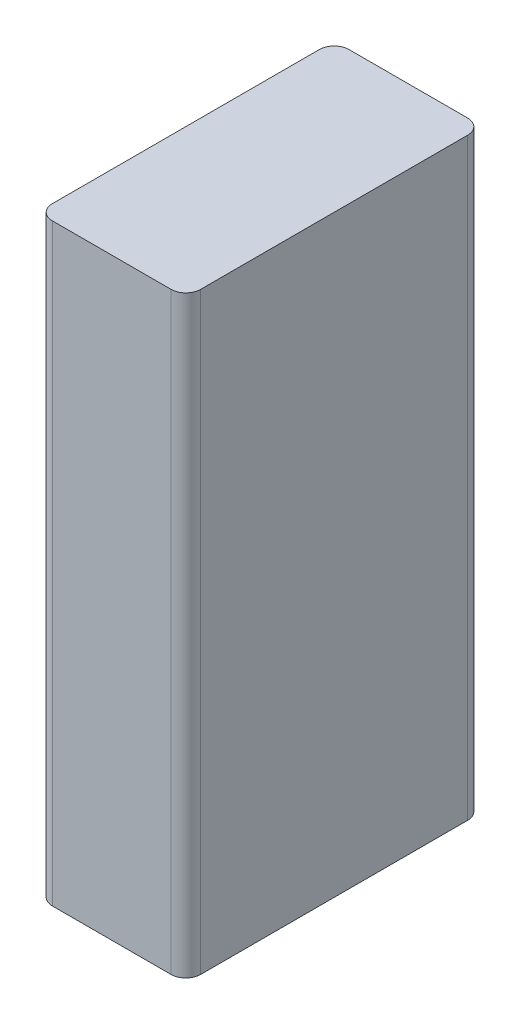
SolidWorks part; units mm, degrees
material "PVC 0.007 Plasticized"
ref_plane "Front Plane" through (0, 0, 0) normal (0, 0, 1) x (1, 0, 0)
ref_plane "Top Plane" through (0, 0, 0) normal (0, 1, 0) x (1, 0, 0)
ref_plane "Right Plane" through (0, 0, 0) normal (1, 0, 0) x (0, 0, -1)
sketch "Sketch1" plane through (0, 0, 0) normal (0, 1, 0) x (1, 0, 0)
  line L1 (-5, -10) -> (5, -10)
  line L2 (-5, -10) -> (-5, 10)
  line L3 (-5, 10) -> (5, 10)
  line L4 (5, -10) -> (5, 10)
  line L5 (-5, -10) -> (5, 10) construction
  line L6 (-5, 10) -> (5, -10) construction
  point P0 (0, 0)
  dimension "D1" = 10
  dimension "D2" = 20
extrude "Boss-Extrude1" add sketch "Sketch1" along normal blind 40
fillet "Fillet1" radius 1 4 edges at (5, 20, -10) (-5, 20, -10) (5, 20, 10) (-5, 20, 10)
